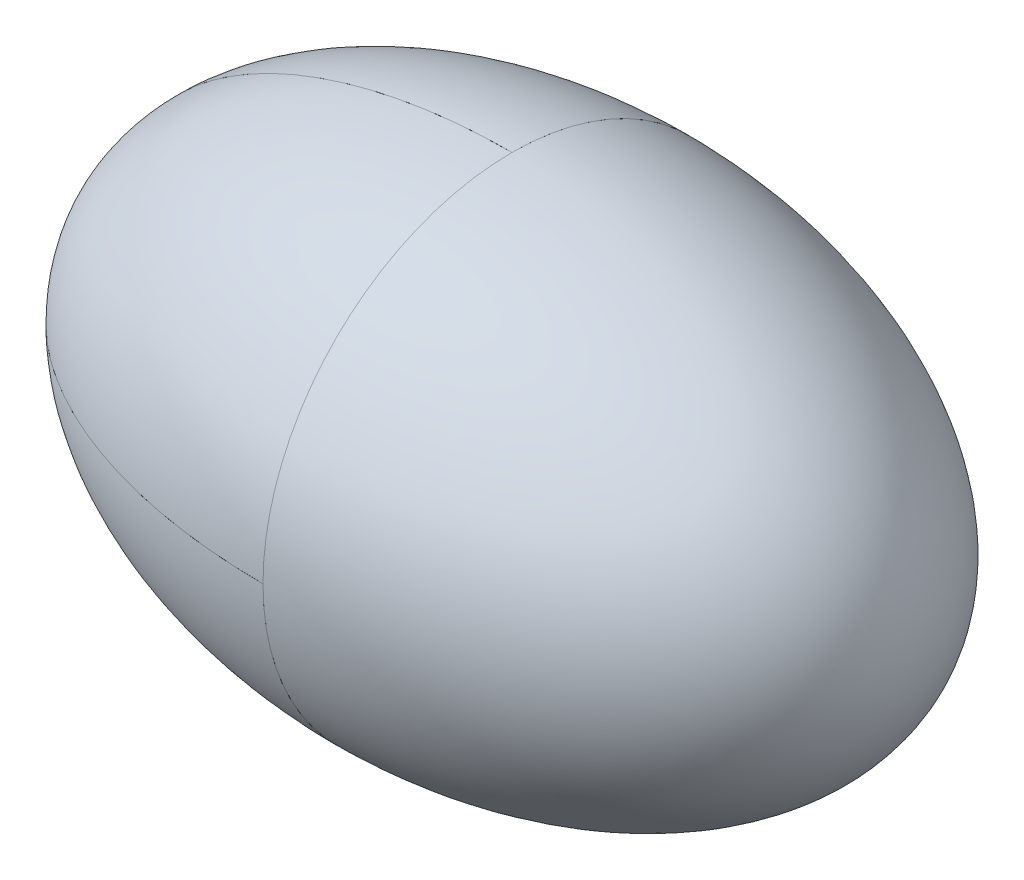
SolidWorks part; units mm, degrees
material "Natural Rubber"
ref_plane "Front Plane" through (0, 0, 0) normal (0, 0, 1) x (1, 0, 0)
ref_plane "Top Plane" through (0, 0, 0) normal (0, 1, 0) x (1, 0, 0)
ref_plane "Right Plane" through (0, 0, 0) normal (1, 0, 0) x (0, 0, -1)
sketch "Sketch1" plane through (0, 0, 0) normal (0, 0, 1) x (1, 0, 0)
  line L0 (-134.62, 0) -> (0, 0)
  line L1 (-134.62, 0) -> (0, 0) construction
  line L2 (0, 85.09) -> (0, 0)
  ellipse E0 centre (0, 0) end of major axis (134.62, 0) minor radius 85.09 (0, 85.09) -> (-134.62, 0) ccw
revolve "Revolve2" add sketch "Sketch1" angle 90 about L1
sketch "Sketch3" plane through (0, 0, 0) normal (0, 0, 1) x (1, 0, 0)
  line L0 (-134.62, 0) -> (0, 0)
  line L1 (-134.62, 85.09) -> (134.62, 85.09)
  line L2 (-134.62, 85.09) -> (-134.62, -85.09)
  line L3 (-134.62, -85.09) -> (134.62, -85.09)
  line L4 (134.62, 85.09) -> (134.62, -85.09)
  line L5 (-134.62, 85.09) -> (134.62, -85.09) construction
  line L6 (-134.62, -85.09) -> (134.62, 85.09) construction
  line L7 (0, 0) -> (0, -85.09)
  ellipse E0 centre (0, 0) end of major axis (134.62, 0) minor radius 85.09 (-134.62, 0) -> (0, -85.09) ccw
  point P0 (0, 0)
  dimension "D1" = 170.18
  dimension "D2" = 269.24
revolve "Revolve3" add sketch "Sketch3" angle 90 about L0
sketch "Sketch4" plane through (0, 0, 0) normal (0, 0, -1) x (-1, 0, 0)
  line L1 (0, 0) -> (134.62, 0)
  line L2 (0, 85.09) -> (0, 0)
  ellipse E0 centre (0, 0) end of major axis (134.62, 0) minor radius 85.09 (134.62, 0) -> (0, 85.09) ccw
revolve "Revolve5" add sketch "Sketch4" angle 90 about L1
sketch "Sketch5" plane through (0, 0, 0) normal (0, 0, 1) x (1, 0, 0)
  line L0 (-134.62, 0) -> (0, 0)
  line L1 (0, 0) -> (0, -85.09)
  ellipse E0 centre (0, 0) end of major axis (-134.62, 0) minor radius 85.09 (-134.62, 0) -> (0, -85.09) ccw
revolve "Revolve6" add sketch "Sketch5" angle 90 about L0
sketch "Sketch6" plane through (0, 0, 0) normal (0, 0, 1) x (1, 0, 0)
  line L0 (0, 0) -> (134.62, 0)
  line L3 (0, 85.09) -> (0, 0)
  line L4 (134.62, 0) -> (0, 0)
  ellipse E0 centre (0, 0) end of major axis (-134.62, 0) minor radius 85.09 (134.62, 0) -> (0, 85.09) ccw
  point P5 (136.5611, 0)
revolve "Revolve8" add sketch "Sketch6" angle 360 about L0
